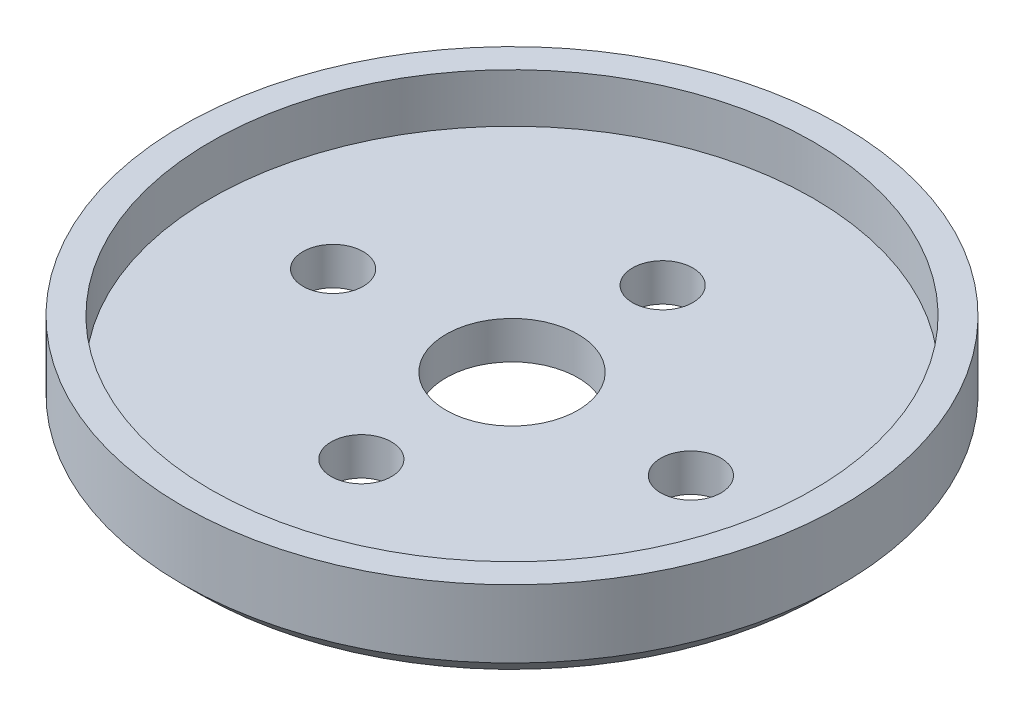
SolidWorks part; units mm, degrees
material "Stainless Steel (ferritic)"
ref_plane "Front Plane" through (0, 0, 0) normal (0, 0, 1) x (1, 0, 0)
ref_plane "Top Plane" through (0, 0, 0) normal (0, 1, 0) x (1, 0, 0)
ref_plane "Right Plane" through (0, 0, 0) normal (1, 0, 0) x (0, 0, -1)
sketch "Sketch1" plane through (0, 0, 0) normal (0, 1, 0) x (1, 0, 0)
  circle A0 centre (0, 0) radius 17.5
  circle A1 centre (0, 0) radius 3.5
  dimension "D1" = 35
  dimension "D2" = 7
extrude "Boss-Extrude1" add sketch "Sketch1" along normal blind 2
sketch "Sketch10" plane through (0, 2, 0) normal (0, 1, 0) x (1, 0, 0)
  circle A0 centre (0, 0) radius 16
  circle A1 centre (0, 0) radius 17.5
  circle A4 centre (0, 0) radius 17.5 construction
  dimension "D1" = 1.5
extrude "Boss-Extrude4" add sketch "Sketch10" along normal offset from surface (2.6 mm away) 4.6 up to face at (0, 0, 17.5)
sketch "Sketch2" plane through (0, 2, 0) normal (0, 1, 0) x (1, 0, 0)
  line L13 (-9.5, 0) -> (9.5, 0) construction
  line L14 (0, -8) -> (0, 8) construction
  circle A1 centre (-9.5, 0) radius 1.6
  circle A3 centre (0, 8) radius 1.6
  circle A5 centre (0, -8) radius 1.6
  circle A8 centre (9.5, 0) radius 1.6
  point P2 (0, 0)
  point P3 (0, 0)
  dimension "D5" = 3.2
  dimension "D1" = 16
  dimension "D4" = 19
extrude "Cut-Extrude1" cut sketch "Sketch2" against normal blind 3
chamfer "Chamfer2" distance 1 angle 45 1 edges at (0, 0, 17.5)
equation "\"HOLE_DIAMETER\"= 3.2mm"
equation "\"D5@Sketch2\"=\"HOLE_DIAMETER\""
